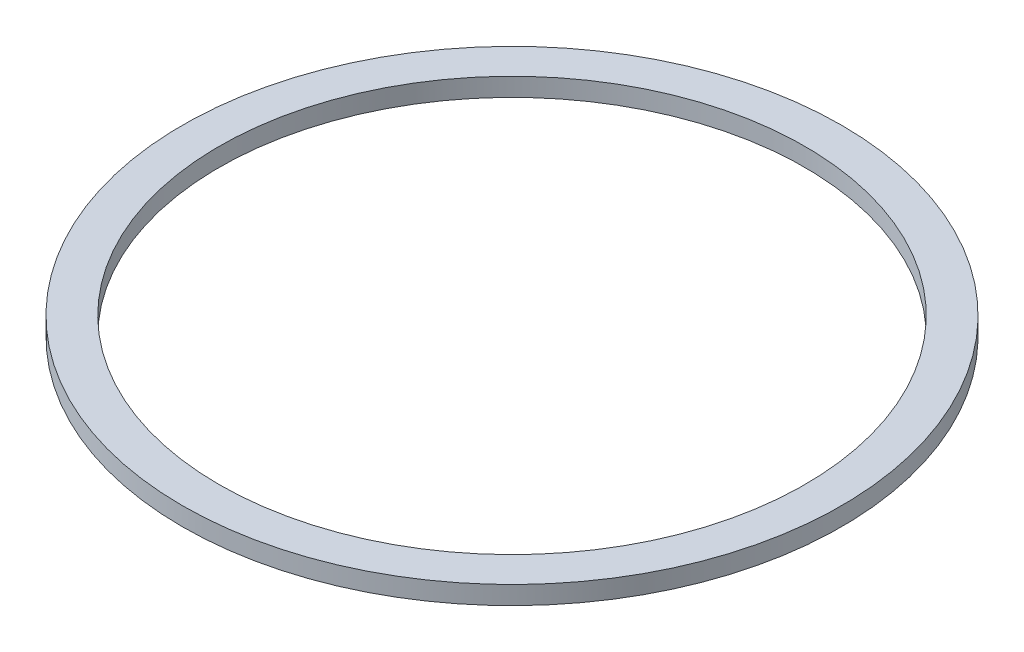
SolidWorks part; units mm, degrees
ref_plane "Plan de face" through (0, 0, 0) normal (0, 0, 1) x (1, 0, 0)
ref_plane "Plan de dessus" through (0, 0, 0) normal (0, 1, 0) x (1, 0, 0)
ref_plane "Plan de droite" through (0, 0, 0) normal (1, 0, 0) x (0, 0, -1)
sketch "Esquisse1" plane through (0, 0, 0) normal (0, 1, 0) x (1, 0, 0)
  circle A0 centre (0, 0) radius 18
  circle A1 centre (0, 0) radius 16
  dimension "D1" = 36
  dimension "D2" = 32
extrude "Boss.-Extru.1" add sketch "Esquisse1" along normal blind 1
